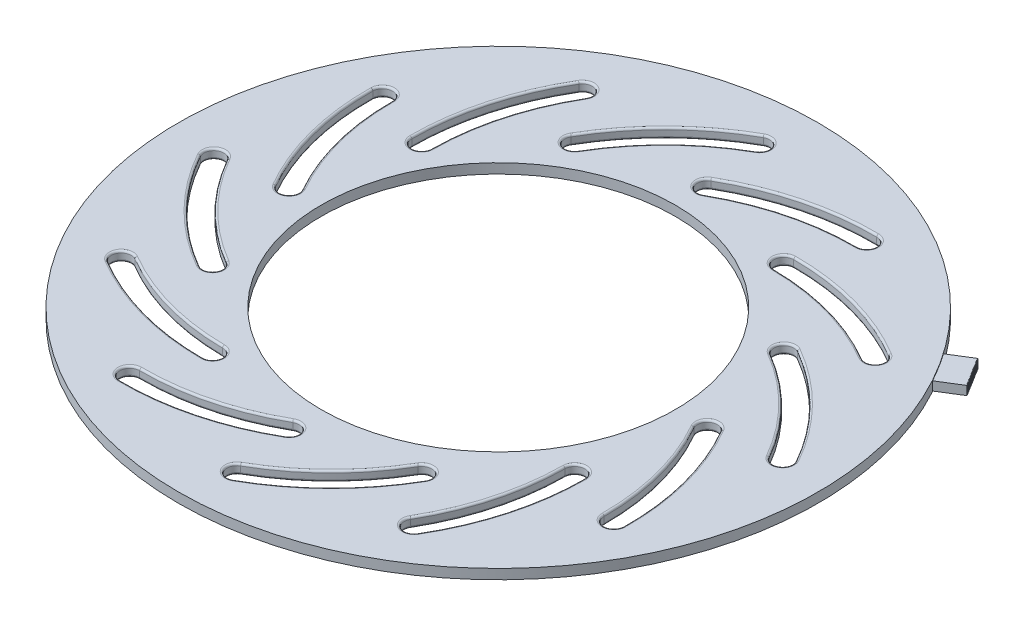
SolidWorks part; units mm, degrees
ref_plane "Front Plane" through (0, 0, 0) normal (0, 0, 1) x (1, 0, 0)
ref_plane "Top Plane" through (0, 0, 0) normal (0, 1, 0) x (1, 0, 0)
ref_plane "Right Plane" through (0, 0, 0) normal (1, 0, 0) x (0, 0, -1)
sketch "sketch 01" plane through (0, 0, 0) normal (0, 1, 0) x (1, 0, 0)
  line L0 (0, 0) -> (28.839, 58.2522) construction
  line L1 (0, 0) -> (65, 0) construction
  line L2 (0, 0) -> (59.1851, 36.7402) construction
  line L3 (-0.0038, -0.0027) -> (68.692, 47.8673) construction
  line L4 (-0.4715, -0.2591) -> (59.4159, 32.6516) construction
  circle A0 centre (0, 0) radius 36
  circle A1 centre (0, 0) radius 65
  point P0 (55.2247, 34.2817)
  dimension "D1" = 130
  dimension "D2" = 72
  dimension "D3" = 63.661
  dimension "D5" = 31.831
  dimension "D7" = 3.04
  dimension "D8" = 3.04
extrude "top ring" add sketch "sketch 01" along normal blind 2
sketch "Sketch2" plane through (0, 2, 0) normal (0, 1, 0) x (1, 0, 0)
  line L0 (0, 0) -> (0, 72.7751) construction
  line L1 (0, 42.5) -> (27.0676, 58.1275) construction
  circle A0 centre (0, 0) radius 55.5 construction
  circle A1 centre (0, 0) radius 42.5 construction
  arc A2 (-1, 44.2321) -> (25.7223, 51.1937) centre (25, -0.8013) cw
  arc A3 (0.9908, 40.7627) -> (25.6774, 47.194) centre (25.2566, -1.7863) cw
  circle A4 centre (25, -0.8013) radius 50 construction
  arc A5 (25.7223, 51.1937) -> (25.6774, 47.194) centre (25.6945, 49.1939) cw
  arc A6 (-1, 44.2321) -> (0.9908, 40.7627) centre (0, 42.5) ccw
  point P19 (0, 42.5)
  dimension "D1" = 85
  dimension "D2" = 111
  dimension "D3" = 100
  dimension "D4" = 60
  dimension "D5" = 2
extrude "Cut-Extrude1" cut sketch "Sketch2" against normal through all contours A3 A5 A2 A6
fillet "Fillet1" radius 0.4 8 edges at (12.908, 0, -45.6137) (27.6944, 0, -49.1714) (27.6944, 2, -49.1714) (-1.7347, 0, -41.5046) (-1.7347, 2, -41.5046) (12.908, 2, -45.6137) (11.8906, 0, -49.5191) (11.8906, 2, -49.5191)
pattern_circular "CirPattern1" count 12 over 360 about axis through (0, 0, 0) along (0, 1, 0) of "Cut-Extrude1", "Fillet1"
ref_plane "Plane1" through (55.2247, 0, -34.2817) normal (0.8496, 0, -0.5274) x (-0.5274, 0, -0.8496)
sketch "Sketch5" plane through (55.2247, 0, -34.2817) normal (0.8496, 0, -0.5274) x (-0.5274, 0, -0.8496)
  line L0 (-3.452, 0.1) -> (3.4516, 0.1)
  line L1 (-3.452, 0) -> (3.4516, 0) construction
  line L2 (-3.452, 0) -> (-3.452, 1.9) construction
  line L3 (-3.452, 1.9) -> (3.4516, 1.9)
  line L4 (3.4516, 0) -> (3.4516, 1.9) construction
  line L5 (65, 2) -> (-65, 2) construction
  line L6 (3.4516, 1.9) -> (3.4516, 0.1)
  line L7 (-3.452, 1.9) -> (-3.452, 0.1)
  line L9 (10606.6522, 0) -> (-10610.2191, 0) construction
  line L12 (-10605.4978, 0) -> (10609.9373, 0) construction
  dimension "D1" = 0.1
  dimension "D2" = 0.1
extrude "Boss-Extrude4" add sketch "Sketch5" along normal blind 5 and the other way up to surface other way up to face at (0, 2, 65)
sketch "Sketch6" plane through (59.4727, 0, -36.9187) normal (0.8496, 0, -0.5274) x (-0.5274, 0, -0.8496)
  line L0 (-2.6866, 0.1) -> (-2.5983, 0.1)
  line L6 (-3.452, 0.1) -> (3.4516, 0.1) construction
  line L7 (-2.6866, 1.9) -> (-2.5983, 1.9)
  line L8 (-2.6866, 1.9) -> (-2.6866, 0.1)
  line L10 (-2.5983, 1.9) -> (-2.5983, 0.1)
extrude "Cut-Extrude2" cut sketch "Sketch6" against normal blind 0.1
pattern_linear "LPattern1" count 5 spacing 0.2 along (0.5274, 0, 0.8496) count 31 spacing 0.2 along (-0.5274, 0, -0.8496) of "Cut-Extrude2"
equation "\"D1@CirPattern1\"=\"grooves@Shutter Assembly.Assembly\""
equation "\"D5@sketch 01\"=\"D3@sketch 01\"/2"
